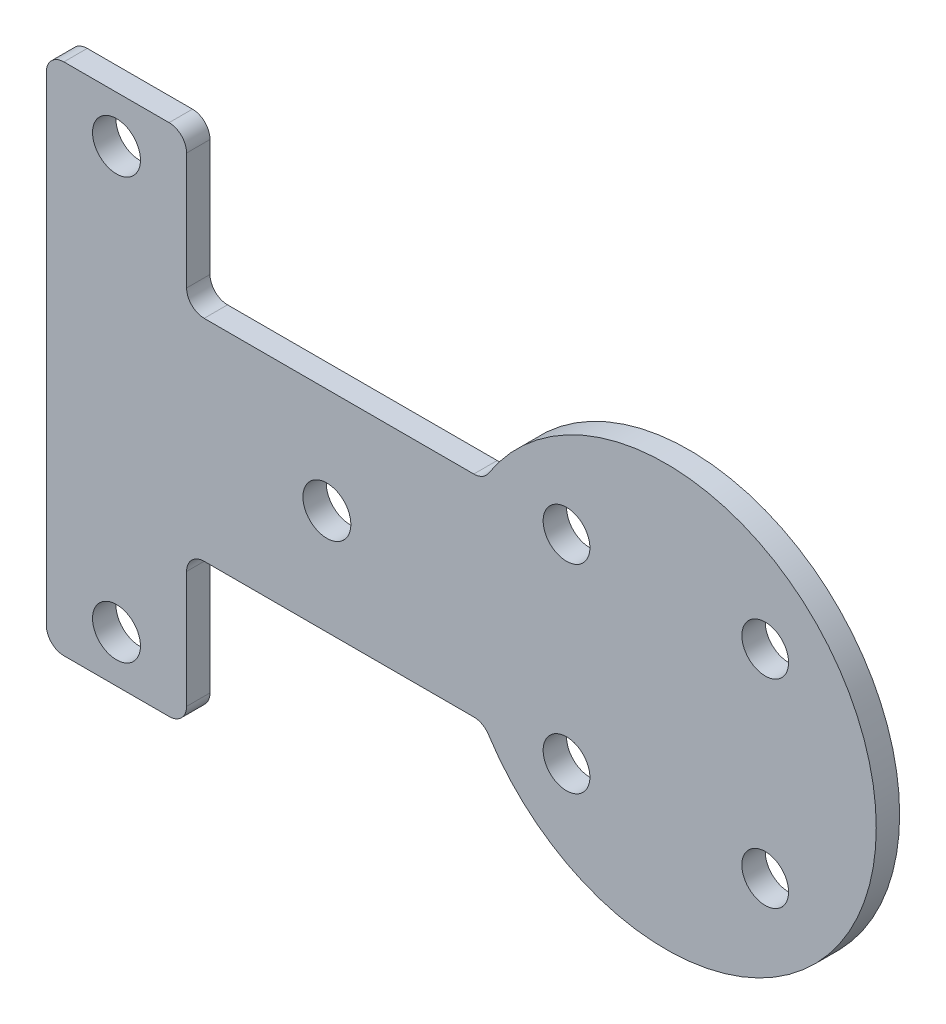
SolidWorks part; units mm, degrees
ref_plane "前视基准面" through (0, 0, 0) normal (0, 0, 1) x (1, 0, 0)
ref_plane "上视基准面" through (0, 0, 0) normal (0, 1, 0) x (1, 0, 0)
ref_plane "右视基准面" through (0, 0, 0) normal (1, 0, 0) x (0, 0, -1)
sketch "草图1" plane through (0, 0, 0) normal (0, 0, 1) x (1, 0, 0)
  line L0 (-42.7236, -13.3699) -> (-17.312, -13.3699)
  line L3 (-42.7236, 4.6301) -> (-42.7236, 17.6301)
  line L4 (-42.7236, 17.6301) -> (-54.7236, 17.6301)
  line L5 (-54.7236, 17.6301) -> (-54.7236, -26.3699)
  line L6 (-54.7236, -26.3699) -> (-42.7236, -26.3699)
  line L7 (-42.7236, -26.3699) -> (-42.7236, -13.3699)
  line L8 (-1.7236, -4.3699) -> (-30.7236, -4.3699) construction
  line L9 (-30.7236, -4.3699) -> (-48.7236, -4.3699) construction
  line L10 (-48.7236, -4.3699) -> (-48.7236, 13.6301) construction
  line L11 (-1.7236, -4.3699) -> (6.7764, -4.3699) construction
  line L12 (6.7764, -4.3699) -> (6.7764, -12.8699) construction
  line L13 (-42.7236, 4.6301) -> (-17.312, 4.6301)
  circle A1 centre (-30.7236, -4.3699) radius 2.05
  circle A2 centre (-48.7236, 13.6301) radius 2.05
  circle A3 centre (-48.7236, -22.3699) radius 2.05
  circle A11 centre (6.7764, -12.8699) radius 2
  circle A12 centre (-10.2236, -12.8699) radius 2
  circle A13 centre (-10.2236, 4.1301) radius 2
  circle A14 centre (6.7764, 4.1301) radius 2
  circle A15 centre (-1.7236, -4.3699) radius 18 construction
  arc A16 (-17.312, -13.3699) -> (-17.312, 4.6301) centre (-1.7236, -4.3699) ccw
  dimension "D1" = 4.1
  dimension "D3" = 4
  dimension "D5" = 36
  dimension "D6" = 18
  dimension "D7" = 12
  dimension "D8" = 29
  dimension "D9" = 6
  dimension "D10" = 18
  dimension "D11" = 4
extrude "凸台-拉伸1" add sketch "草图1" along normal blind 2
fillet "圆角1" radius 1.5 8 edges at (-54.7236, 17.6301, 1) (-42.7236, 17.6301, 1) (-42.7236, -26.3699, 1) (-54.7236, -26.3699, 1) (-17.312, -13.3699, 1) (-17.312, 4.6301, 1) (-42.7236, 4.6301, 1) (-42.7236, -13.3699, 1)
